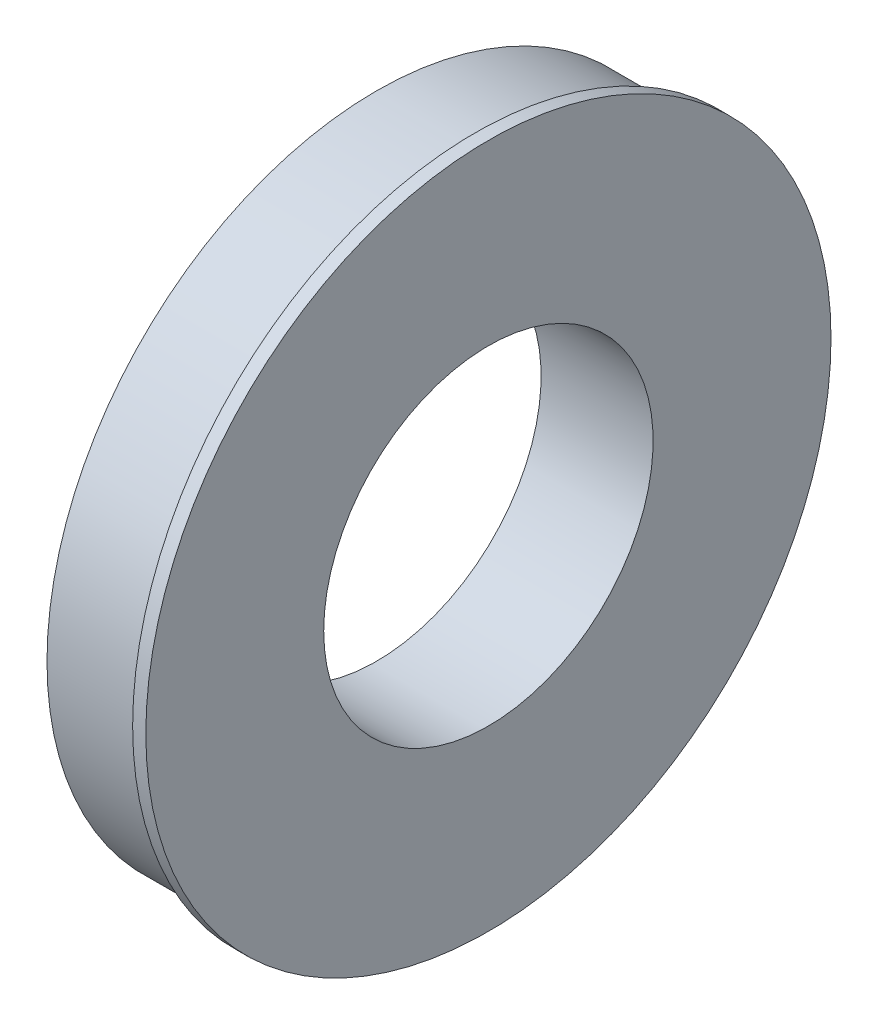
SolidWorks part; units mm, degrees
ref_plane "Front Plane" through (0, 0, 0) normal (0, 0, 1) x (1, 0, 0)
ref_plane "Top Plane" through (0, 0, 0) normal (0, 1, 0) x (1, 0, 0)
ref_plane "Right Plane" through (0, 0, 0) normal (1, 0, 0) x (0, 0, -1)
sketch "Sketch1" plane through (0, 0, 0) normal (1, 0, 0) x (0, 0, -1)
  circle A0 centre (0, 0) radius 31.75
  circle A1 centre (0, 0) radius 63.5
  dimension "D1" = 127
  dimension "D2" = 63.5
extrude "Boss-Extrude1" add sketch "Sketch1" along normal blind 19.05
sketch "Sketch2" plane through (19.05, 0, 0) normal (1, 0, 0) x (0, 0, -1)
  circle A1 centre (0, 0) radius 31.75 construction
  circle A2 centre (0, 0) radius 66.04
  circle A3 centre (0, 0) radius 66.04
  circle A6 centre (0, 0) radius 31.75
  dimension "D1" = 2.54
extrude "Boss-Extrude2" add sketch "Sketch2" along normal blind 2.54
